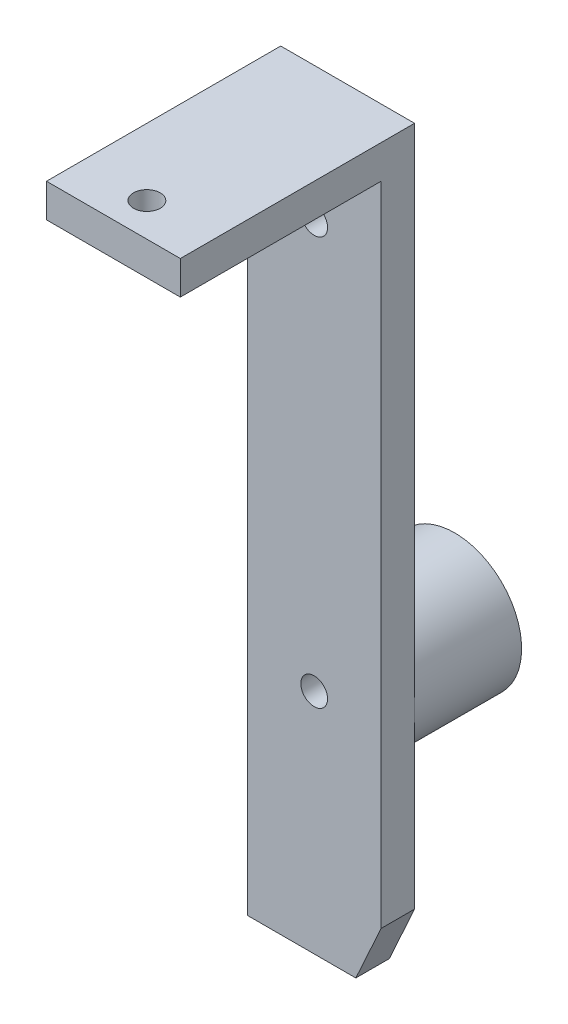
SolidWorks part; units mm, degrees
ref_plane "Front Plane" through (0, 0, 0) normal (0, 0, 1) x (1, 0, 0)
ref_plane "Top Plane" through (0, 0, 0) normal (0, 1, 0) x (1, 0, 0)
ref_plane "Right Plane" through (0, 0, 0) normal (1, 0, 0) x (0, 0, -1)
sketch "Sketch1" plane through (0, 0, 0) normal (0, 1, 0) x (1, 0, 0)
  line L1 (6.35, -1.5875) -> (-6.35, -1.5875)
  line L2 (6.35, -1.5875) -> (6.35, 1.5875)
  line L3 (6.35, 1.5875) -> (-6.35, 1.5875)
  line L4 (-6.35, -1.5875) -> (-6.35, 1.5875)
  line L5 (6.35, -1.5875) -> (-6.35, 1.5875) construction
  line L6 (6.35, 1.5875) -> (-6.35, -1.5875) construction
  point P0 (0, 0)
  dimension "D1" = 3.175
  dimension "D2" = 12.7
extrude "Boss-Extrude1" add sketch "Sketch1" along normal blind 69.85
sketch "Sketch2" plane through (0, 0, 1.5875) normal (0, 0, 1) x (1, 0, 0)
  line L0 (6.35, 69.85) -> (6.35, 0) construction
  line L1 (-6.35, 69.85) -> (6.35, 69.85)
  line L2 (-6.35, 69.85) -> (-6.35, 66.675)
  line L3 (-6.35, 66.675) -> (6.35, 66.675)
  line L4 (6.35, 69.85) -> (6.35, 66.675)
  dimension "D1" = 3.175
extrude "Boss-Extrude2" add sketch "Sketch2" along normal blind 19.05
sketch "Sketch3" plane through (0, 66.675, 0) normal (0, -1, 0) x (1, 0, 0)
  line L0 (0, 20.6375) -> (0, -1.5875) construction
  line L1 (-6.35, 20.6375) -> (6.35, 20.6375) construction
  line L2 (6.35, -1.5875) -> (-6.35, -1.5875) construction
  circle A0 centre (0, 17.4625) radius 1.27
  dimension "D1" = 2.54
  dimension "D2" = 19.05
extrude "Cut-Extrude1" cut sketch "Sketch3" against normal through all
sketch "Sketch4" plane through (0, 0, 1.5875) normal (0, 0, 1) x (1, 0, 0)
  line L0 (0, 66.675) -> (0, 0) construction
  line L1 (-6.35, 66.675) -> (6.35, 66.675) construction
  line L2 (-6.35, 0) -> (6.35, 0) construction
  circle A0 centre (0, 21.59) radius 1.27
  circle A1 centre (0, 60.325) radius 1.27
  dimension "D1" = 2.54
  dimension "D3" = 2.54
  dimension "D2" = 21.59
  dimension "D4" = 6.35
extrude "Cut-Extrude2" cut sketch "Sketch4" against normal through all
sketch "Sketch5" plane through (0, 0, -1.5875) normal (0, 0, -1) x (-1, 0, 0)
  circle A0 centre (0, 21.59) radius 1.27 construction
  circle A1 centre (0, 21.59) radius 1.27
  circle A2 centre (0, 21.59) radius 6.35
  dimension "D1" = 12.7
extrude "Boss-Extrude3" add sketch "Sketch5" along normal blind 10.16
sketch "Sketch6" plane through (0, 0, 1.5875) normal (0, 0, 1) x (1, 0, 0)
  line L0 (3.9515, 0) -> (6.35, 5.2717)
  line L1 (-6.35, 0) -> (6.35, 0) construction
  line L2 (6.35, 66.675) -> (6.35, 0) construction
  line L3 (6.35, 5.2717) -> (6.35, 0)
  line L4 (6.35, 0) -> (3.9515, 0)
extrude "Cut-Extrude3" cut sketch "Sketch6" against normal through all
